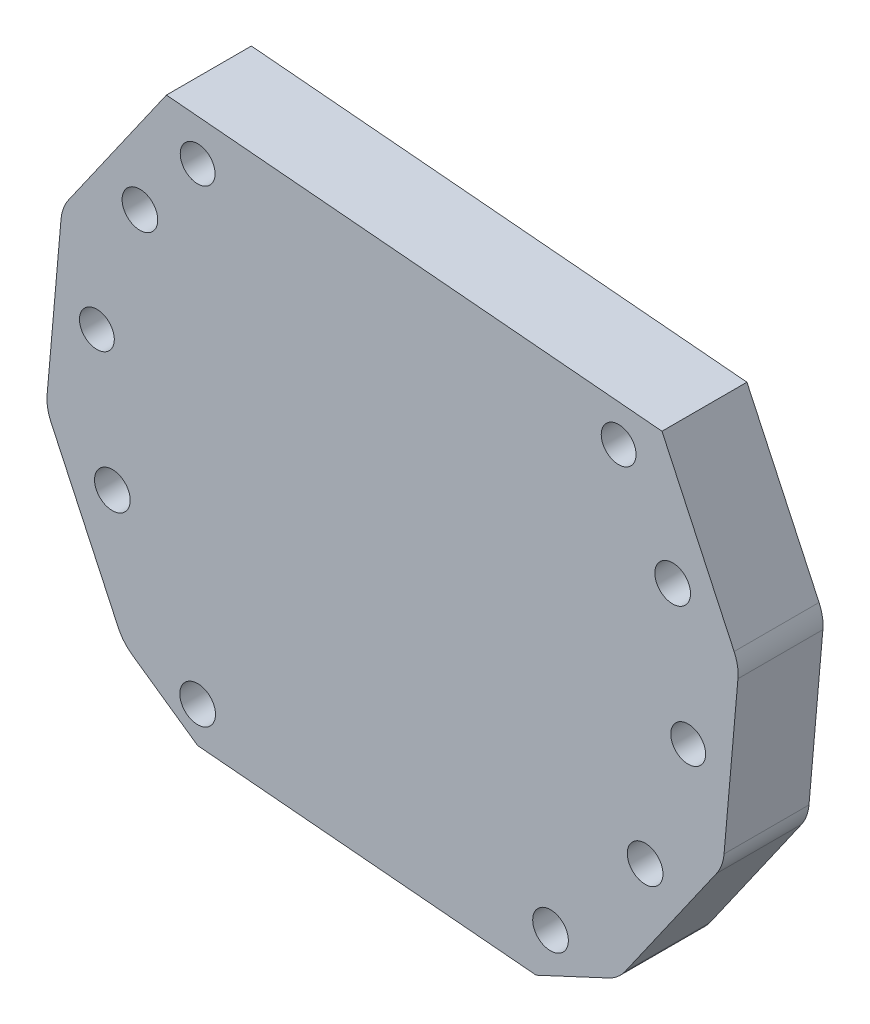
SolidWorks part; units mm, degrees
material "PP copolymère"
ref_plane "Plan de face" through (0, 0, 0) normal (0, 0, 1) x (1, 0, 0)
ref_plane "Plan de dessus" through (0, 0, 0) normal (0, 1, 0) x (1, 0, 0)
ref_plane "Plan de droite" through (0, 0, 0) normal (1, 0, 0) x (0, 0, -1)
sketch "Esquisse1" plane through (0, 0, 0) normal (0, 0, 1) x (1, 0, 0)
  line L0 (16.9047, -36.2523) -> (26.6185, -31.7227)
  line L2 (-26.6185, 31.7227) -> (-38.9137, 14.1634)
  line L3 (-38.9137, 14.1634) -> (-40.7819, -7.191)
  line L4 (-40.7819, -7.191) -> (-31.7227, -26.6185)
  line L5 (-31.7227, -26.6185) -> (-22.9431, -32.7661)
  line L7 (26.6185, -31.7227) -> (38.9137, -14.1634)
  line L8 (38.9137, -14.1634) -> (40.7819, 7.191)
  line L9 (40.7819, 7.191) -> (31.7227, 26.6185)
  line L12 (-26.6185, 31.7227) -> (31.7227, 26.6185)
  line L13 (16.9047, -36.2523) -> (-22.9431, -32.7661)
  line L15 (-7.191, 40.7819) -> (-26.6185, 31.7227) [skipped]
  line L16 (14.1634, 38.9137) -> (-7.191, 40.7819) [skipped]
  line L17 (31.7227, 26.6185) -> (14.1634, 38.9137) [skipped]
  line L18 (-14.1634, -38.9137) -> (7.191, -40.7819) [skipped]
  arc A0 (-26.6185, 31.7227) -> (-31.7227, -26.6185) centre (0, 0) ccw construction
  arc A1 (26.6185, -31.7227) -> (31.7227, 26.6185) centre (0, 0) ccw construction
  dimension "D1" = 80
extrude "Boss.-Extru.1" add sketch "Esquisse1" along normal blind 10
sketch "Esquisse3" plane through (0, 0, 0) normal (0, 0, -1) x (-1, 0, 0)
  circle A0 centre (-26.6185, 22.7059) radius 2.05
  circle A1 centre (22.9431, 26.5543) radius 2.05
  circle A2 centre (29.7378, 18.4699) radius 2.1
  circle A3 centre (34.8067, 3.7381) radius 2.05
  circle A4 centre (32.9816, -11.7341) radius 2.1
  circle A5 centre (22.9431, -28.5378) radius 2.1
  circle A6 centre (-18.6013, -30.822) radius 2.1
  circle A7 centre (-29.7378, -18.4699) radius 2.1
  circle A8 centre (-34.8067, -3.7381) radius 2.05
  circle A9 centre (-32.9816, 11.7341) radius 2.1
  dimension "D1" = 4.1
  dimension "D2" = 4.1
  dimension "D3" = 4.1
  dimension "D4" = 4.1
  dimension "D5" = 4.2
extrude "Enlèv. mat.-Extru.1" cut sketch "Esquisse3" against normal through all
fillet "Congé1" radius 5 6 edges at (-31.7227, -26.6185, 5) (-40.7819, -7.191, 5) (-38.9137, 14.1634, 5) (40.7819, 7.191, 5) (26.6185, -31.7227, 5) (38.9137, -14.1634, 5)
